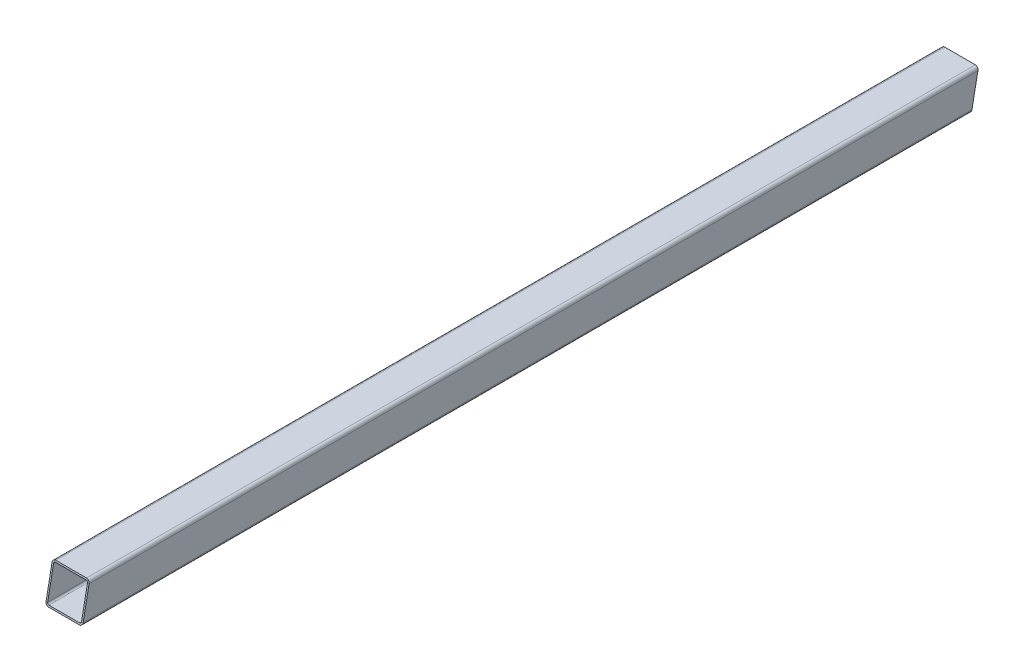
SolidWorks part; units mm, degrees
material "ASTM A36 Steel"
ref_plane "Front Plane" through (0, 0, 0) normal (0, 0, 1) x (1, 0, 0)
ref_plane "Top Plane" through (0, 0, 0) normal (0, 1, 0) x (1, 0, 0)
ref_plane "Right Plane" through (0, 0, 0) normal (1, 0, 0) x (0, 0, -1)
sketch "Sketch1" plane through (0, 0, 0) normal (0, 0, 1) x (1, 0, 0)
  line L1 (17.467, 34.0143) -> (-40.533, 34.0143)
  line L2 (20.467, 31.0143) -> (20.467, -26.9857)
  line L3 (17.467, -29.9857) -> (-40.533, -29.9857)
  line L4 (-43.533, 31.0143) -> (-43.533, -26.9857)
  line L5 (17.467, 37.0143) -> (-40.533, 37.0143)
  line L6 (23.467, 31.0143) -> (23.467, -26.9857)
  line L7 (17.467, -32.9857) -> (-40.533, -32.9857)
  line L8 (-46.533, 31.0143) -> (-46.533, -26.9857)
  arc A0 (17.467, 37.0143) -> (23.467, 31.0143) centre (17.467, 31.0143) cw
  arc A1 (23.467, -26.9857) -> (17.467, -32.9857) centre (17.467, -26.9857) cw
  arc A2 (-40.533, -32.9857) -> (-46.533, -26.9857) centre (-40.533, -26.9857) cw
  arc A3 (-46.533, 31.0143) -> (-40.533, 37.0143) centre (-40.533, 31.0143) cw
  arc A4 (20.467, -26.9857) -> (17.467, -29.9857) centre (17.467, -26.9857) cw
  arc A5 (-40.533, -29.9857) -> (-43.533, -26.9857) centre (-40.533, -26.9857) cw
  arc A6 (-43.533, 31.0143) -> (-40.533, 34.0143) centre (-40.533, 31.0143) cw
  arc A7 (20.467, 31.0143) -> (17.467, 34.0143) centre (17.467, 31.0143) ccw
  arc A8 (20.467, 31.0143) -> (17.467, 34.0143) centre (17.467, 31.0143) ccw
  arc A9 (20.467, 31.0143) -> (17.467, 34.0143) centre (17.467, 31.0143) ccw
  arc A10 (20.467, 31.0143) -> (17.467, 34.0143) centre (17.467, 31.0143) ccw
  arc A11 (20.467, 31.0143) -> (17.467, 34.0143) centre (17.467, 31.0143) ccw
  arc A12 (20.467, 31.0143) -> (17.467, 34.0143) centre (17.467, 31.0143) ccw
  arc A13 (20.467, 31.0143) -> (17.467, 34.0143) centre (17.467, 31.0143) ccw
  point P10 (23.467, 37.0143)
  point P15 (-46.533, -32.9857)
  point P18 (-46.533, 37.0143)
  point P21 (20.467, -29.9857)
  point P24 (-43.533, -29.9857)
  point P27 (-43.533, 34.0143)
  dimension "D7" = 6
  dimension "D8" = 3
  dimension "D9" = 3
  dimension "D10" = 3
  dimension "D11" = 3
  dimension "D12" = 3
  dimension "D13" = 3
  dimension "D14" = 3
  dimension "D1" = 70
  dimension "D2" = 70
  dimension "D3" = 64
  dimension "D4" = 64
  dimension "D5" = 3
  dimension "D6" = 3
extrude "Boss-Extrude1" add sketch "Sketch1" along normal blind 1693 contours A3 L8 A2 L7 A1 L6 A0 L5 A7 L2 A4 L3 A5 L4 A6 L1
sketch "Sketch2" plane through (23.467, 0, 0) normal (1, 0, 0) x (0, 0, -1)
  line L0 (0, -32.9857) -> (-13.6, -32.9857)
  line L1 (-1693, -32.9857) -> (0, -32.9857) construction
  line L2 (-13.6, -32.9857) -> (0, 37.0143)
  line L3 (0, 37.0143) -> (0, -32.9857)
  line L4 (-1679.4, 37.0143) -> (-1693, 37.0143)
  line L5 (-1679.4, 37.0143) -> (-1693, -32.9857)
  line L6 (-1693, 37.0143) -> (0, 37.0143) construction
  line L7 (-1693, 37.0143) -> (-1693, -32.9857)
  dimension "D1" = 13.6
  dimension "D2" = 13.6
  dimension "D3" = 1679.4
extrude "Cut-Extrude1" cut sketch "Sketch2" against normal blind 1214
